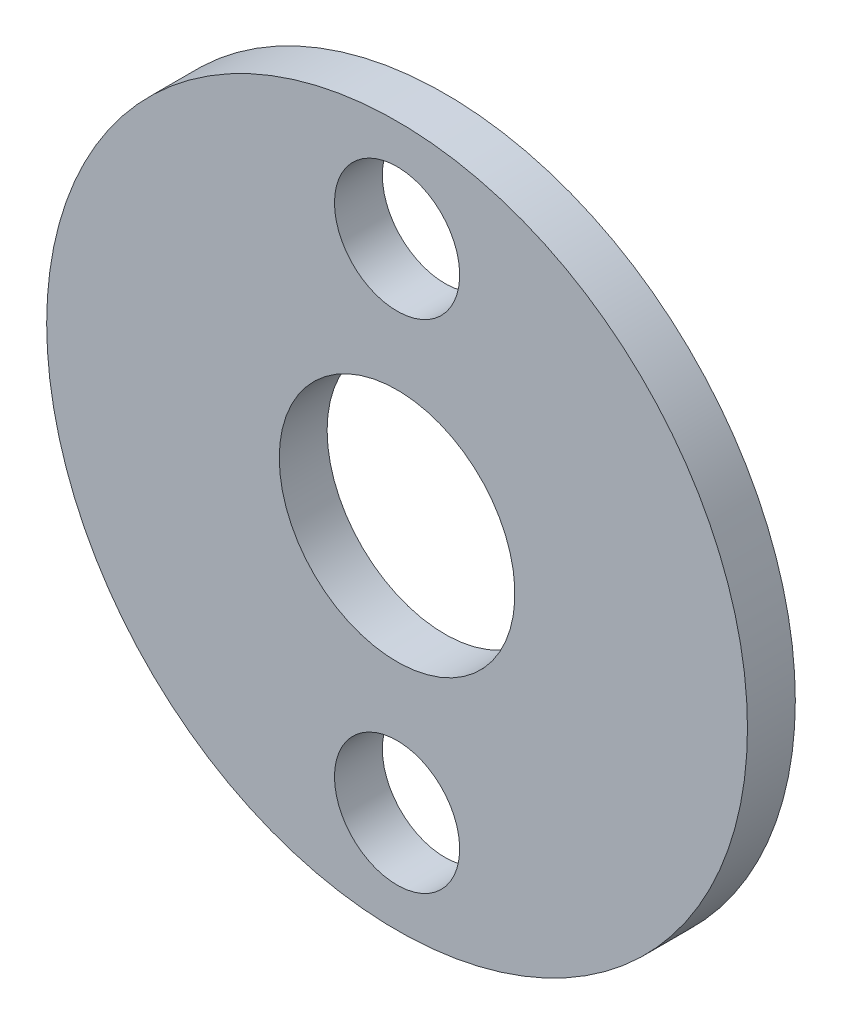
SolidWorks part; units mm, degrees
ref_plane "Front Plane" through (0, 0, 0) normal (0, 0, 1) x (1, 0, 0)
ref_plane "Top Plane" through (0, 0, 0) normal (0, 1, 0) x (1, 0, 0)
ref_plane "Right Plane" through (0, 0, 0) normal (1, 0, 0) x (0, 0, -1)
sketch "Sketch1" plane through (0, 0, 0) normal (0, 0, 1) x (1, 0, 0)
  line L0 (0, 8.5725) -> (0, -8.5725) construction
  circle A0 centre (0, 0) radius 12.0872
  circle A2 centre (0, 0) radius 4.064
  circle A5 centre (0, 8.5725) radius 2.159
  circle A6 centre (0, -8.5725) radius 2.159
  dimension "D1" = 24.1743
  dimension "D2" = 8.128
  dimension "D4" = 4.318
  dimension "D3" = 17.145
extrude "Boss-Extrude1" add sketch "Sketch1" along normal blind 1.651
